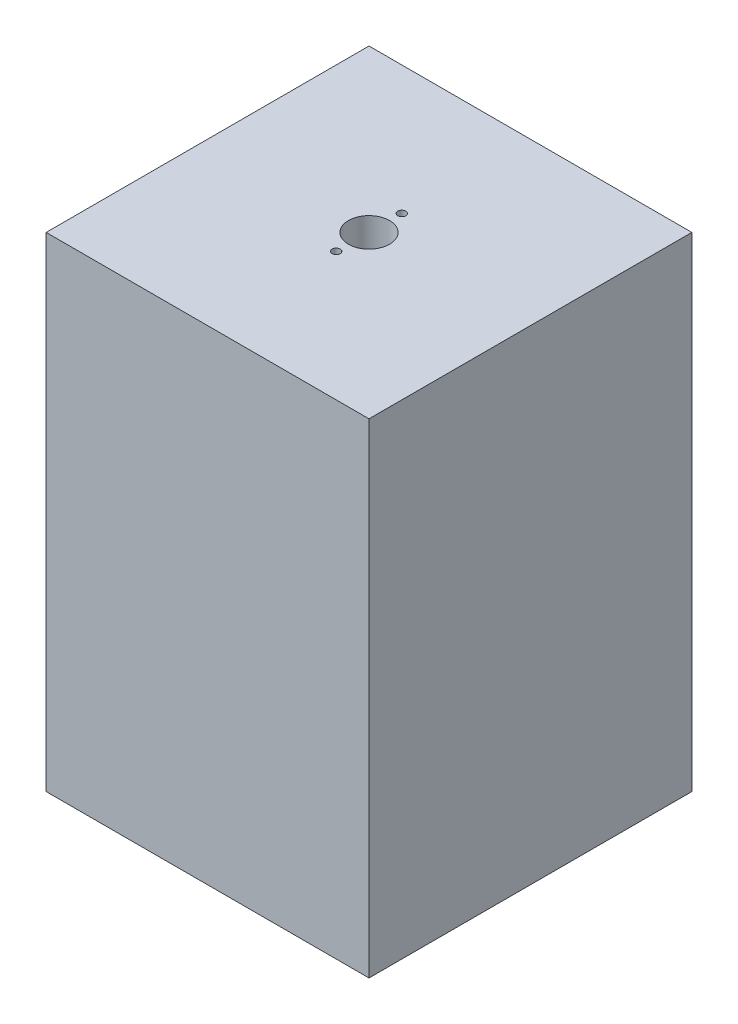
SolidWorks part; units mm, degrees
material "6061 Alloy"
ref_plane "Front Plane" through (0, 0, 0) normal (0, 0, 1) x (1, 0, 0)
ref_plane "Top Plane" through (0, 0, 0) normal (0, 1, 0) x (1, 0, 0)
ref_plane "Right Plane" through (0, 0, 0) normal (1, 0, 0) x (0, 0, -1)
sketch "Sketch1" plane through (0, 0, 0) normal (0, 1, 0) x (1, 0, 0)
  line L1 (-50.8, -50.8) -> (50.8, -50.8)
  line L2 (-50.8, -50.8) -> (-50.8, 50.8)
  line L3 (-50.8, 50.8) -> (50.8, 50.8)
  line L4 (50.8, -50.8) -> (50.8, 50.8)
  line L5 (-50.8, -50.8) -> (50.8, 50.8) construction
  line L6 (-50.8, 50.8) -> (50.8, -50.8) construction
  point P0 (0, 0)
  dimension "D1" = 101.6
extrude "Boss-Extrude1" add sketch "Sketch1" along normal mid plane 152.4
sketch "Sketch2" plane through (0, 76.2, 0) normal (0, 1, 0) x (1, 0, 0)
  line L0 (0, -10.3251) -> (0, 10.3251) construction
  circle A0 centre (0, 0) radius 6.477
  circle A1 centre (0, 10.3251) radius 1.27
  circle A2 centre (0, -10.3251) radius 1.27
  dimension "D1" = 2.54
  dimension "D2" = 12.954
  dimension "D3" = 10.3251
extrude "Cut-Extrude1" cut sketch "Sketch2" against normal blind 12.7
